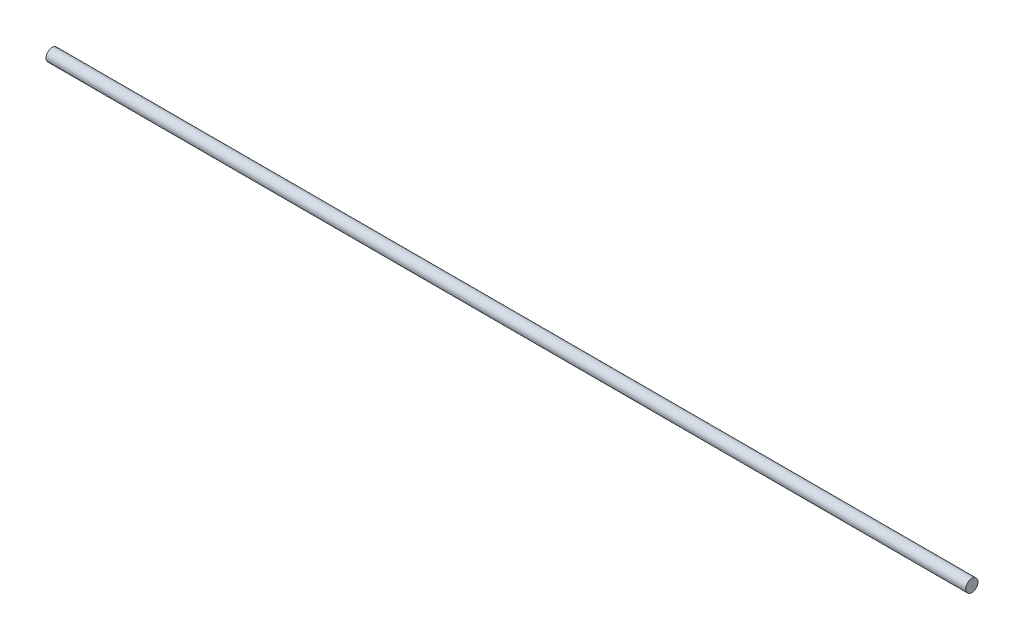
SolidWorks part; units mm, degrees
material "AISI Type 316L stainless steel"
ref_plane "Front Plane" through (0, 0, 0) normal (0, 0, 1) x (1, 0, 0)
ref_plane "Top Plane" through (0, 0, 0) normal (0, 1, 0) x (1, 0, 0)
ref_plane "Right Plane" through (0, 0, 0) normal (1, 0, 0) x (0, 0, -1)
sketch "Sketch1" plane through (0, 0, 0) normal (1, 0, 0) x (0, 0, -1)
  circle A0 centre (0, 0) radius 4
  dimension "D1" = 8
extrude "Boss-Extrude1" add sketch "Sketch1" along normal mid plane 600
